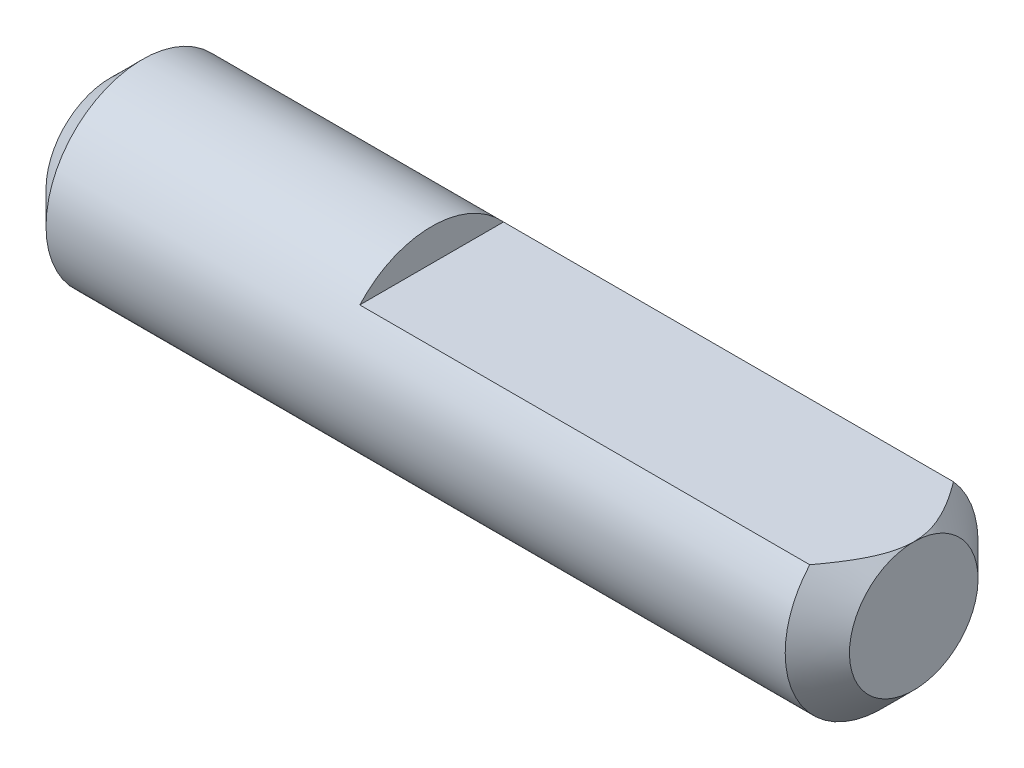
SolidWorks part; units mm, degrees
ref_plane "Front Plane" through (0, 0, 0) normal (0, 0, 1) x (1, 0, 0)
ref_plane "Top Plane" through (0, 0, 0) normal (0, 1, 0) x (1, 0, 0)
ref_plane "Right Plane" through (0, 0, 0) normal (1, 0, 0) x (0, 0, -1)
sketch "Sketch1" plane through (0, 0, 0) normal (0, 0, 1) x (1, 0, 0)
  line L0 (-12.5, 0) -> (12.5, 0) construction
  line L1 (-12.5, -3) -> (12.5, -3)
  line L2 (-12.5, -3) -> (-12.5, 3)
  line L3 (-12.5, 3) -> (12.5, 3)
  line L4 (12.5, -3) -> (12.5, 3)
  point P4 (0, 3)
  point P5 (-12.5, 0)
  dimension "D1" = 6
  dimension "D2" = 25
revolve "Revolve1" add sketch "Sketch1" angle 360 about L0
chamfer "Chamfer1" distance 1 angle 45 2 edges at (-12.5, 0, 3) (12.5, 0, 3)
sketch "Sketch2" plane through (0, 0, 0) normal (0, 0, 1) x (1, 0, 0)
  line L0 (12.5, -2) -> (12.5, 2) construction
  line L1 (12.5, 2) -> (-2.5, 2)
  line L2 (12.5, 2) -> (12.5, 3)
  line L3 (12.5, 3) -> (-2.5, 3)
  line L4 (-2.5, 2) -> (-2.5, 3)
  line L5 (11.5, 3) -> (-11.5, 3) construction
  dimension "D1" = 15
  dimension "D2" = 1
extrude "Cut-Extrude1" cut sketch "Sketch2" against normal through all and the other way through all
